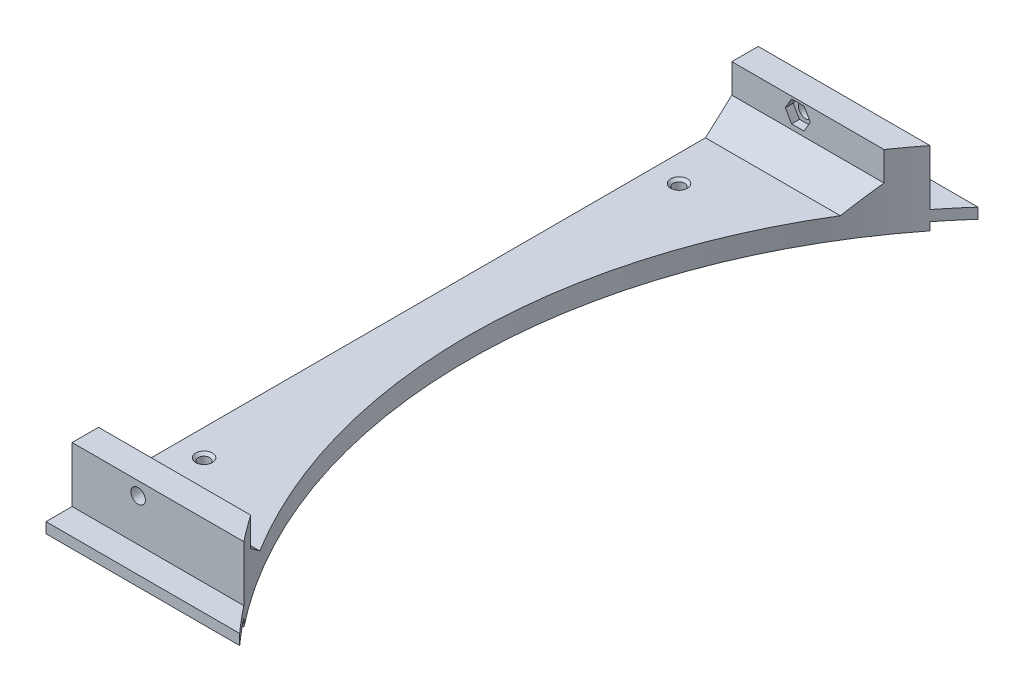
SolidWorks part; units mm, degrees
ref_plane "Front Plane" through (0, 0, 0) normal (0, 0, 1) x (1, 0, 0)
ref_plane "Top Plane" through (0, 0, 0) normal (0, 1, 0) x (1, 0, 0)
ref_plane "Right Plane" through (0, 0, 0) normal (1, 0, 0) x (0, 0, -1)
sketch "Sketch1" plane through (0, 0, 0) normal (0, 1, 0) x (1, 0, 0)
  line L0 (0, 0) -> (0, 650)
  line L1 (0, 650) -> (650, 650)
  line L2 (650, 650) -> (650, 0)
  line L3 (650, 0) -> (0, 0)
  dimension "D1" = 650
  dimension "D2" = 650
extrude "Boss-Extrude1" add sketch "Sketch1" along normal blind 8
sketch "Sketch3" plane through (0, 0, 0) normal (0, 0, 1) x (1, 0, 0)
  line L0 (325, 8) -> (325, 43.7071) construction
  line L1 (0, 8) -> (650, 8) construction
  line L2 (300, 43.7071) -> (350, 43.7071)
  line L3 (300, 43.7071) -> (265, 8)
  line L4 (265, 8) -> (385, 8)
  line L5 (385, 8) -> (350, 43.7071)
  point P7 (325, 43.7071)
  dimension "D1" = 50
  dimension "D2" = 50
  dimension "D3" = 50
  dimension "D4" = 120
extrude "Boss-Extrude2" add sketch "Sketch3" against normal blind 650
sketch "Sketch4" plane through (0, 0, 0) normal (0, 0, 1) x (1, 0, 0)
  line L0 (265, 8) -> (385, 8) construction
  circle A0 centre (325, 22) radius 11
  dimension "D1" = 14
extrude "Cut-Extrude2" cut sketch "Sketch4" against normal through all both and the other way through all
sketch "Sketch2" plane through (0, 8, 0) normal (0, 1, 0) x (1, 0, 0)
  line L0 (0, 650) -> (0, 0) construction
  line L1 (650, 650) -> (385, 650) construction
  circle A0 centre (325, 325) radius 210
  dimension "D3" = 420
  dimension "D1" = 325
  dimension "D2" = 325
extrude "Cut-Extrude1" cut sketch "Sketch2" against normal through all both and the other way through all
sketch "Sketch5" plane through (0, 0, 0) normal (0, 0, 1) x (1, 0, 0)
  line L0 (300, 43.7071) -> (350, 43.7071)
  line L1 (265, 8) -> (385, 8) construction
  line L2 (300, 8) -> (300, 28)
  line L3 (300, 8) -> (350, 8)
  line L4 (350, 8) -> (350, 28)
  line L5 (350, 28) -> (365.3961, 28)
  line L6 (385, 8) -> (350, 43.7071) construction
  line L7 (365.3961, 28) -> (350, 43.7071)
  line L8 (300, 28) -> (284.6039, 28)
  line L9 (300, 43.7071) -> (265, 8) construction
  line L10 (284.6039, 28) -> (300, 43.7071)
extrude "Cut-Extrude3" cut sketch "Sketch5" against normal blind 110 and the other way through all
sketch "Sketch6" plane through (0, 0, -650) normal (0, 0, -1) x (-1, 0, 0)
  line L0 (-265, 8) -> (-385, 8) construction
  line L1 (-350, 43.7071) -> (-300, 43.7071)
  line L2 (-300, 8) -> (-300, 28)
  line L3 (-300, 28) -> (-284.6039, 28)
  line L4 (-300, 43.7071) -> (-265, 8) construction
  line L5 (-284.6039, 28) -> (-300, 43.7071)
  line L6 (-350, 8) -> (-350, 28)
  line L7 (-350, 28) -> (-365.3961, 28)
  line L8 (-365.3961, 28) -> (-350, 43.7071)
  line L9 (-350, 8) -> (-300, 8)
extrude "Cut-Extrude4" cut sketch "Sketch6" against normal blind 110
sketch "Sketch7" plane through (0, 8, 0) normal (0, 1, 0) x (1, 0, 0)
  line L1 (325, 325) -> (325, 455) construction
  line L2 (325, 325) -> (325, 195) construction
  line L3 (325, 325) -> (455, 325) construction
  line L4 (325, 325) -> (195, 325) construction
  line L9 (325, 455) -> (455, 455) construction
  line L10 (455, 455) -> (455, 195) construction
  line L11 (455, 195) -> (195, 195) construction
  line L12 (195, 195) -> (195, 455) construction
  line L13 (195, 455) -> (325, 455) construction
  line L14 (195, 455) -> (-124.315, 455)
  line L15 (-124.315, 455) -> (-40.6133, 195)
  line L16 (-40.6133, 195) -> (195, 195)
  line L17 (195, 195) -> (195, 455)
  dimension "D1" = 130
  dimension "D2" = 130
  dimension "D3" = 130
  dimension "D4" = 130
extrude "Cut-Extrude5" cut sketch "Sketch7" against normal through all both and the other way through all flip side to cut
sketch "Sketch8" plane through (0, 0, 0) normal (-1, 0, 0) x (0, 0, 1)
  line L0 (-455, 8) -> (-455, 28)
  line L1 (-455, 28) -> (-445, 28)
  line L2 (-445, 28) -> (-445, 17)
  line L3 (-445, 17) -> (-435, 8)
  line L4 (-455, 8) -> (-195, 8) construction
  line L5 (-435, 8) -> (-455, 8)
  line L6 (-195, 8) -> (-195, 28)
  line L7 (-195, 28) -> (-205, 28)
  line L11 (-205, 17) -> (-215, 8)
  line L12 (-205, 28) -> (-205, 17)
  line L13 (-215, 8) -> (-195, 8)
  dimension "D1" = 20
  dimension "D2" = 10
  dimension "D3" = 10
  dimension "D4" = 20
  dimension "D5" = 20
  dimension "D6" = 20
  dimension "D7" = 11
  dimension "D8" = 11
extrude "Boss-Extrude3" add sketch "Sketch8" against normal blind 170
sketch "Sketch11" plane through (0, 0, 0) normal (-1, 0, 0) x (0, 0, 1)
  line L0 (-455, 3) -> (-455, 7)
  line L1 (-455, 0) -> (-455, 28) construction
  line L2 (-455, 7) -> (-464.9, 7)
  line L3 (-464.9, 7) -> (-464.9, 3)
  line L4 (-464.9, 3) -> (-455, 3)
  line L5 (-195, 3) -> (-185.1, 3)
  line L6 (-195, 28) -> (-195, 0) construction
  line L7 (-195, 3) -> (-195, 7)
  line L8 (-195, 7) -> (-185.1, 7)
  line L9 (-185.1, 7) -> (-185.1, 3)
  line L10 (-455, 0) -> (-195, 0) construction
  dimension "D1" = 3
  dimension "D2" = 4
  dimension "D3" = 4
  dimension "D4" = 9.9
  dimension "D5" = 9.9
extrude "Boss-Extrude4" add sketch "Sketch11" against normal blind 170
sketch "Sketch10" plane through (0, 8, 0) normal (0, 1, 0) x (1, 0, 0)
  line L0 (0, 0) -> (0, 650) construction
  line L1 (0, 650) -> (650, 650) construction
  line L2 (650, 650) -> (0, 0) construction
  circle A0 centre (325, 325) radius 210
extrude "Cut-Extrude7" cut sketch "Sketch10" against normal through all both and the other way through all
sketch "Sketch12" plane through (0, 0, -195) normal (0, 0, 1) x (1, 0, 0)
  line L0 (0, 28) -> (0, 7) construction
  line L1 (160.0758, 28) -> (0, 28) construction
  circle A0 centre (40, 23) radius 2.75
  circle A1 centre (80, 23) radius 2.2
  circle A2 centre (120, 23) radius 2.75
  dimension "D1" = 40
  dimension "D4" = 5.5
  dimension "D5" = 4.4
  dimension "D6" = 5.5
  dimension "D2" = 40
  dimension "D3" = 40
  dimension "D7" = 5
  dimension "D8" = 5
  dimension "D9" = 5
extrude "Cut-Extrude8" cut sketch "Sketch12" against normal through all both and the other way through all
sketch "Sketch13" plane through (0, 8, 0) normal (0, 1, 0) x (1, 0, 0)
  line L0 (115, 266.3474) -> (115, 325) construction
  line L1 (115, 325) -> (95, 325) construction
  line L2 (95, 464.9) -> (95, 185.1)
  line L3 (168.3859, 185.1) -> (0, 185.1) construction
  line L4 (95, 185.1) -> (0, 185.1)
  line L5 (0, 185.1) -> (0, 464.9)
  line L6 (0, 464.9) -> (95, 464.9)
  arc A0 (146.1146, 435) -> (146.1146, 215) centre (325, 325) ccw construction
  point P12 (95, 325)
extrude "Cut-Extrude9" cut sketch "Sketch13" against normal through all both and the other way through all
sketch "Sketch14" plane through (0, 8, 0) normal (0, 1, 0) x (1, 0, 0)
  line L0 (95, 435) -> (95, 215) construction
  line L1 (146.1146, 435) -> (95, 435) construction
  line L2 (146.1146, 215) -> (95, 215) construction
  circle A0 centre (105, 235) radius 2.15
  circle A1 centre (105, 415) radius 2.15
  dimension "D1" = 4.3
  dimension "D2" = 4.3
  dimension "D3" = 10
  dimension "D4" = 10
  dimension "D5" = 20
  dimension "D6" = 20
extrude "Cut-Extrude10" cut sketch "Sketch14" against normal through all both and the other way through all
chamfer "Chamfer1" distance 1 angle 45 3 edges at (105, 8, -417.15) (105, 0, -412.85) (105, 8, -237.15)
sketch "Sketch15" plane through (0, 0, -205) normal (0, 0, -1) x (-1, 0, 0)
  line L0 (-120, 23) -> (-120, 27.1) construction
  line L1 (-120, 23) -> (-120, 18.9) construction
  line L2 (-122.3671, 27.1) -> (-117.6329, 27.1)
  line L3 (-122.3671, 18.9) -> (-117.6329, 18.9)
  line L4 (-117.6329, 27.1) -> (-115.2657, 23)
  line L5 (-115.2657, 23) -> (-117.6329, 18.9)
  line L6 (-122.3671, 18.9) -> (-124.7343, 23)
  line L7 (-124.7343, 23) -> (-122.3671, 27.1)
  point P7 (-120, 27.1)
  point P10 (-120, 18.9)
  dimension "D3" = 120
extrude "Cut-Extrude11" cut sketch "Sketch15" against normal blind 3
pattern_linear "LPattern1" count 2 spacing 243 along (0, 0, -1) of "Cut-Extrude11"
